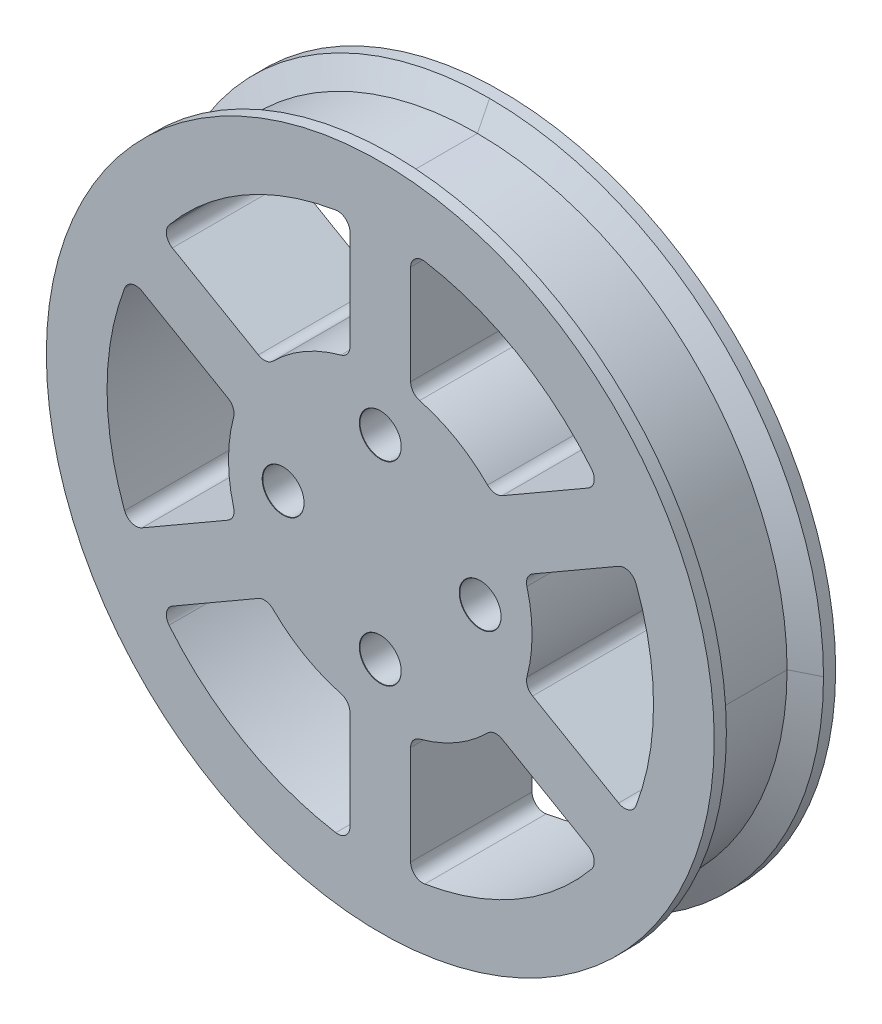
SolidWorks part; units mm, degrees
ref_plane "Спереди" through (0, 0, 0) normal (0, 0, 1) x (1, 0, 0)
ref_plane "Сверху" through (0, 0, 0) normal (0, 1, 0) x (1, 0, 0)
ref_plane "Справа" through (0, 0, 0) normal (1, 0, 0) x (0, 0, -1)
sketch "Эскиз1" plane through (0, 0, 0) normal (0, 0, 1) x (1, 0, 0)
  circle A0 centre (0, 0) radius 27.5
  dimension "D1" = 55
extrude "Бобышка-Вытянуть1" add sketch "Эскиз1" along normal blind 10
ref_plane "Плоскость1" through (0, 0, 5) normal (0, 0, 1) x (1, 0, 0)
sketch "Эскиз2" plane through (0, 0, 10) normal (0, 0, 1) x (1, 0, 0)
  circle A0 centre (0, 0) radius 22.5
  dimension "D1" = 45
extrude "Вырез-Вытянуть1" cut sketch "Эскиз2" against normal up to next
sketch "Эскиз3" plane through (0, 0, 0) normal (0, 0, 1) x (1, 0, 0)
  circle A0 centre (0, 0) radius 12.5
  dimension "D1" = 25
extrude "Бобышка-Вытянуть2" add sketch "Эскиз3" along normal blind 10 separate body
sketch "Эскиз5" plane through (0, 0, 0) normal (0, 0, 1) x (1, 0, 0)
  line L0 (9.3566, 8.2888) -> (18.1149, 13.3454)
  line L1 (2.5, 12.2474) -> (2.5, 22.3607)
  line L2 (2.5, 12.2474) -> (-2.5, 12.2474) construction
  line L3 (-2.5, 12.2474) -> (-2.5, 22.3607)
  line L4 (11.8566, 3.9587) -> (20.6149, 9.0153)
  line L5 (11.8566, -3.9587) -> (20.6149, -9.0153)
  line L6 (9.3566, -8.2888) -> (18.1149, -13.3454)
  line L7 (2.5, -12.2474) -> (2.5, -22.3607)
  line L8 (-2.5, -12.2474) -> (-2.5, -22.3607)
  line L9 (-9.3566, -8.2888) -> (-18.1149, -13.3454)
  line L10 (-11.8566, -3.9587) -> (-20.6149, -9.0153)
  line L11 (-11.8566, 3.9587) -> (-20.6149, 9.0153)
  line L12 (-9.3566, 8.2888) -> (-18.1149, 13.3454)
  circle A0 centre (0, 0) radius 22.5 construction
  circle A1 centre (0, 0) radius 22.5 construction
  circle A2 centre (0, 0) radius 12.5 construction
  arc A3 (-2.5, 12.2474) -> (2.5, 12.2474) centre (0, 0) cw
  arc A4 (-2.5, 22.3607) -> (2.5, 22.3607) centre (0, 0) cw
  arc A5 (18.1149, 13.3454) -> (20.6149, 9.0153) centre (0, 0) cw
  arc A6 (9.3566, 8.2888) -> (11.8566, 3.9587) centre (0, 0) cw
  arc A7 (20.6149, -9.0153) -> (18.1149, -13.3454) centre (0, 0) cw
  arc A8 (11.8566, -3.9587) -> (9.3566, -8.2888) centre (0, 0) cw
  arc A9 (2.5, -22.3607) -> (-2.5, -22.3607) centre (0, 0) cw
  arc A10 (2.5, -12.2474) -> (-2.5, -12.2474) centre (0, 0) cw
  arc A11 (-18.1149, -13.3454) -> (-20.6149, -9.0153) centre (0, 0) cw
  arc A12 (-9.3566, -8.2888) -> (-11.8566, -3.9587) centre (0, 0) cw
  arc A13 (-20.6149, 9.0153) -> (-18.1149, 13.3454) centre (0, 0) cw
  arc A14 (-11.8566, 3.9587) -> (-9.3566, 8.2888) centre (0, 0) cw
  point P56 (0, 0)
  dimension "D1" = 5
  dimension "D2" = 6
extrude "Бобышка-Вытянуть3" add sketch "Эскиз5" along normal blind 10
hole_wizard "Отверстие с зазором M32" positions "Эскиз10" profile "Эскиз11" hole size "M3" standard "DIN" end condition through all
sketch "Эскиз10" plane through (0, 0, 10) normal (0, 0, 1) x (1, 0, 0)
  circle A0 centre (-8, 0) radius 1.575 construction
  circle A1 centre (0, 8) radius 1.575 construction
  circle A2 centre (8.2251, 0) radius 1.575 construction
  circle A3 centre (0, -8) radius 1.575 construction
  circle A4 centre (-8, 0) radius 1.575 construction
  circle A5 centre (0, 8) radius 1.575 construction
  circle A6 centre (8.2251, 0) radius 1.575 construction
  circle A7 centre (0, -8) radius 1.575 construction
  point P0 (-8, 0)
  point P2 (0, 8)
  point P4 (8.2251, 0)
  point P6 (0, -8)
sketch "Эскиз11" plane through (-8, 0, 10) normal (1, 0, 0) x (0, -1, 0)
  line L0 (0, 0) -> (0, 10)
  line L1 (0, 10) -> (1.7, 10)
  line L2 (1.7, 10) -> (1.7, 0.025)
  line L3 (1.7, 0.025) -> (1.725, 0)
  line L5 (1.725, 0) -> (0, 0)
  line L6 (-1.7, 0.025) -> (-1.725, 0) construction
  line L11 (0, -6.35) -> (0, 107.95) construction
  dimension "Диаметр сквозного отверстия" = 3.4
  dimension "Глубина сквозного отверстия" = 10
  dimension "Диаметр передней зенковки" = 3.45
  dimension "Угол передней зенковки" = 90
fillet "Скругление1" radius 1 24 edges at (9.3566, -8.2888, 5) (2.5, -12.2474, 5) (2.5, -22.3607, 5) (18.1149, -13.3454, 5) (-9.3566, -8.2888, 5) (-2.5, -12.2474, 5) (-2.5, -22.3607, 5) (-18.1149, -13.3454, 5) (11.8566, -3.9587, 5) (20.6149, -9.0153, 5) (20.6149, 9.0153, 5) (11.8566, 3.9587, 5) (2.5, 12.2474, 5) (2.5, 22.3607, 5) (18.1149, 13.3454, 5) (9.3566, 8.2888, 5) (-2.5, 12.2474, 5) (-2.5, 22.3607, 5) (-18.1149, 13.3454, 5) (-9.3566, 8.2888, 5) (-20.6149, 9.0153, 5) (-11.8566, -3.9587, 5) (-11.8566, 3.9587, 5) (-20.6149, -9.0153, 5)
sketch "Эскиз13" plane through (0, 0, 0) normal (1, 0, 0) x (0, 0, -1)
  line L0 (0, 27.5) -> (-10, 27.5) construction
  line L1 (0, 27.5) -> (-10, 27.5) construction
  line L3 (0, -27.5) -> (0, 27.5) construction
  line L4 (-8, 25.5) -> (-2, 25.5)
  line L5 (-8, 25.5) -> (-8, 27.5) construction
  line L6 (-8, 27.5) -> (-2, 27.5) construction
  line L7 (-2, 25.5) -> (-2, 27.5) construction
  line L8 (-8, 25.5) -> (-2, 27.5) construction
  line L9 (-8, 27.5) -> (-2, 25.5) construction
  line L10 (-2, 25.5) -> (-1, 27.5)
  line L11 (-8, 25.5) -> (-9, 27.5)
  line L12 (-9, 27.5) -> (-1, 27.5)
  point P2 (-5, 26.5)
  point P5 (-5, 27.5)
  dimension "D1" = 2
  dimension "D2" = 2
  dimension "D3" = 1
sweep "Вырез-По траектории2" cut profiles "Эскиз13" path edge at (27.5, 0, 10)
ref_plane "Плоскость между" through (0, 0, 5) normal (0, 0, 1) x (1, 0, 0)
equation "\"k_сжатия\"= 27.5мм"
